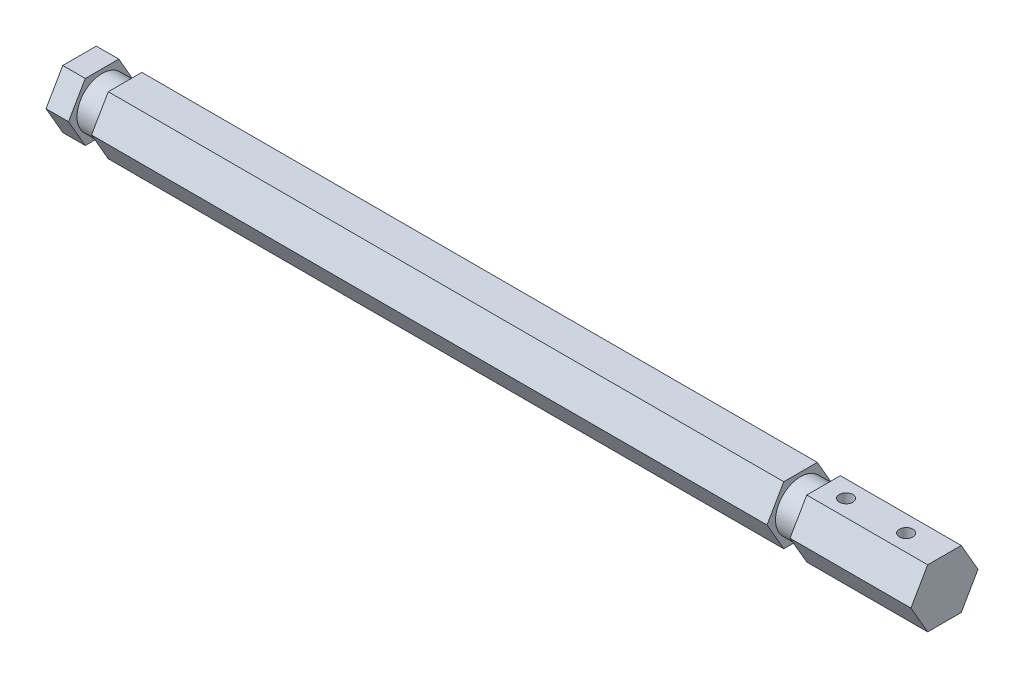
SolidWorks part; units mm, degrees
ref_plane "Front Plane" through (0, 0, 0) normal (0, 0, 1) x (1, 0, 0)
ref_plane "Top Plane" through (0, 0, 0) normal (0, 1, 0) x (1, 0, 0)
ref_plane "Right Plane" through (0, 0, 0) normal (1, 0, 0) x (0, 0, -1)
other "Default"
sketch "Sketch1" plane through (0, 0, 0) normal (1, 0, 0) x (0, 0, -1)
  line L1 (7.4478, 0) -> (3.7239, 6.45)
  line L2 (3.7239, 6.45) -> (-3.7239, 6.45)
  line L3 (-3.7239, 6.45) -> (-7.4478, 0)
  line L4 (-7.4478, 0) -> (-3.7239, -6.45)
  line L5 (-3.7239, -6.45) -> (3.7239, -6.45)
  line L6 (3.7239, -6.45) -> (7.4478, 0)
  circle A0 centre (0, 0) radius 6.45 construction
  dimension "D1" = 12.9
extrude "Boss-Extrude1" add sketch "Sketch1" along normal mid plane 192.06
sketch "Sketch2" plane through (0, 0, 0) normal (0, 0, 1) x (1, 0, 0)
  line L6 (-251.2633, 0) -> (264.9905, 0) construction
  line L7 (-96.03, 6.45) -> (-96.03, 0) construction
  line L8 (-91.03, 5.5562) -> (-85.9246, 5.5562)
  line L9 (-91.03, 5.5562) -> (-91.03, 11.45)
  line L10 (-91.03, 11.45) -> (-85.9246, 11.45)
  line L11 (-85.9246, 5.5562) -> (-85.9246, 11.45)
  line L12 (96.03, 6.45) -> (-96.03, 6.45) construction
  line L14 (64.0754, 5.5562) -> (69.1808, 5.5562)
  line L15 (64.0754, 5.5562) -> (64.0754, 11.45)
  line L16 (64.0754, 11.45) -> (69.1808, 11.45)
  line L17 (69.1808, 5.5562) -> (69.1808, 11.45)
  dimension "D1" = 5
  dimension "D2" = 5.1054
  dimension "D3" = 11.1125
  dimension "D4" = 5
  dimension "D5" = 150
revolve "Cut-Revolve1" cut sketch "Sketch2" angle 360 about L6
sketch "Sketch3" plane through (0, 6.45, 0) normal (0, 1, 0) x (1, 0, 0)
  line L0 (69.1808, 5.5562) -> (69.1808, -5.5562) construction
  circle A0 centre (74.1808, 0) radius 1.5
  circle A1 centre (87.5308, 0) radius 1.5
  dimension "D1" = 3
  dimension "D2" = 5
  dimension "D3" = 13.35
extrude "Cut-Extrude1" cut sketch "Sketch3" against normal through all
